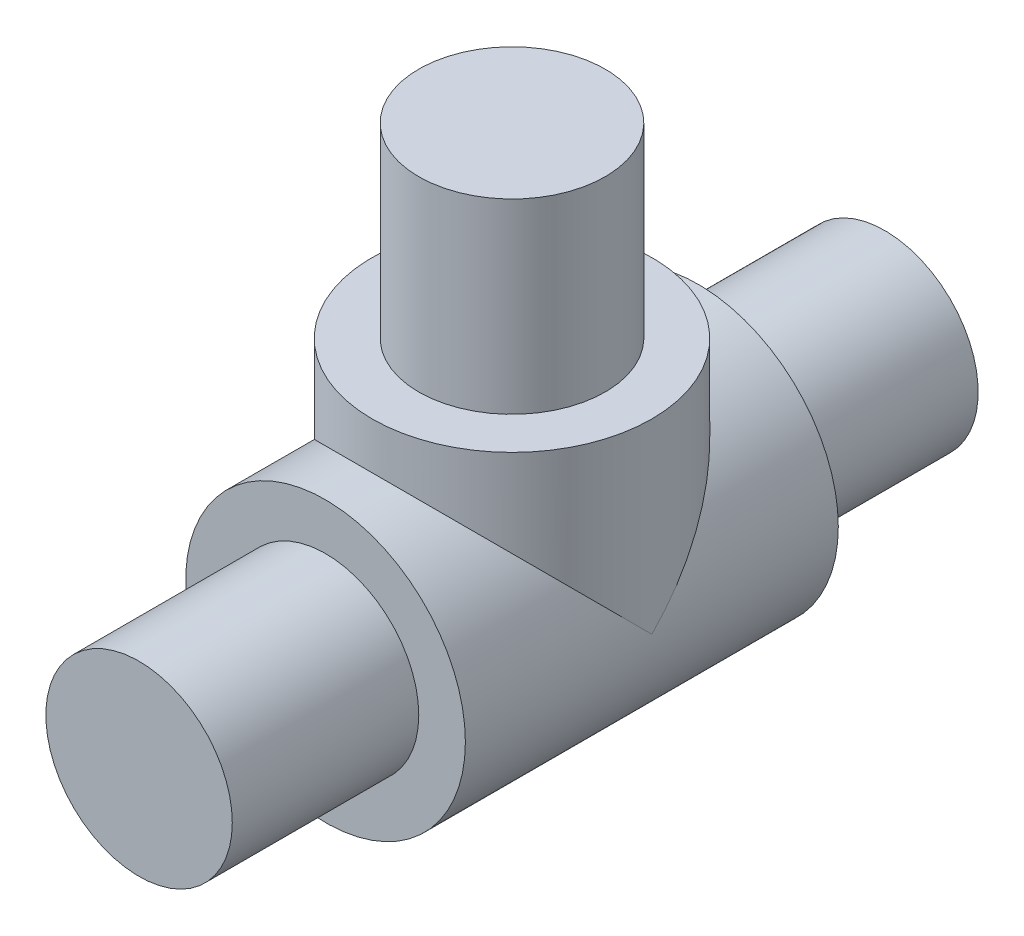
SolidWorks part; units mm, degrees
ref_plane "Front" through (0, 0, 0) normal (0, 0, 1) x (1, 0, 0)
ref_plane "Top" through (0, 0, 0) normal (0, 1, 0) x (1, 0, 0)
ref_plane "Right" through (0, 0, 0) normal (1, 0, 0) x (0, 0, -1)
sketch "Sketch2" plane through (0, 0, 0) normal (0, 0, 1) x (1, 0, 0)
  circle A0 centre (0, 0) radius 3.81
  dimension "D1" = 7.62
extrude "Boss-Extrude1" add sketch "Sketch2" along normal blind 10.16
sketch "Sketch3" plane through (0, 0, 10.16) normal (0, 0, 1) x (1, 0, 0)
  circle A0 centre (0, 0) radius 2.54
  dimension "D1" = 5.08
extrude "Boss-Extrude2" add sketch "Sketch3" along normal blind 5.08
sketch "Sketch4" plane through (0, 0, 0) normal (0, 0, -1) x (-1, 0, 0)
  circle A0 centre (0, 0) radius 2.54
  dimension "D1" = 5.08
extrude "Boss-Extrude3" add sketch "Sketch4" along normal blind 5.08
sketch "Sketch5" plane through (0, 0, 0) normal (0, 1, 0) x (1, 0, 0)
  line L0 (3.81, 0) -> (-3.81, 0) construction
  circle A0 centre (0, -5.08) radius 3.81
  point P2 (0, 0)
  point P3 (0, 0)
  dimension "D1" = 5.08
  dimension "D2" = 7.62
extrude "Boss-Extrude4" add sketch "Sketch5" along normal blind 5.08
sketch "Sketch6" plane through (0, 5.08, 0) normal (0, 1, 0) x (1, 0, 0)
  circle A0 centre (0, -5.08) radius 2.54
  circle A1 centre (0, -5.08) radius 3.81 construction
  dimension "D1" = 5.08
extrude "Boss-Extrude5" add sketch "Sketch6" along normal blind 5.08
